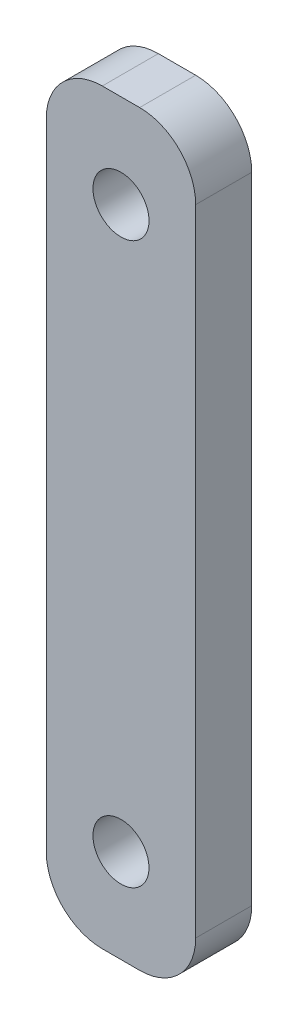
SolidWorks part; units mm, degrees
ref_plane "Alzado" through (0, 0, 0) normal (0, 0, 1) x (1, 0, 0)
ref_plane "Planta" through (0, 0, 0) normal (0, 1, 0) x (1, 0, 0)
ref_plane "Vista lateral" through (0, 0, 0) normal (1, 0, 0) x (0, 0, -1)
sketch "Croquis1" plane through (0, 0, 0) normal (0, 0, 1) x (1, 0, 0)
  line L0 (0, -51.8487) -> (0, 74.7456) construction
  line L1 (-1, -20) -> (1, -20)
  line L2 (-4, -17) -> (-4, 17)
  line L3 (-1, 20) -> (1, 20)
  line L4 (4, -17) -> (4, 17)
  line L5 (-4, -20) -> (4, 20) construction
  line L6 (-4, 20) -> (4, -20) construction
  line L7 (23.9085, 0) -> (-18.7658, 0) construction
  circle A0 centre (0, 15) radius 1.5
  circle A1 centre (0, -15) radius 1.5
  arc A2 (1, -20) -> (4, -17) centre (1, -17) ccw
  arc A3 (-1, -20) -> (-4, -17) centre (-1, -17) cw
  arc A4 (1, 20) -> (4, 17) centre (1, 17) cw
  arc A5 (-4, 17) -> (-1, 20) centre (-1, 17) cw
  point P0 (0, 0)
  point P12 (0, 0)
  dimension "D3" = 3
  dimension "D5" = 3
  dimension "D1" = 8
  dimension "D2" = 40
  dimension "D4" = 5
extrude "Saliente-Extruir1" add sketch "Croquis1" along normal mid plane 3
